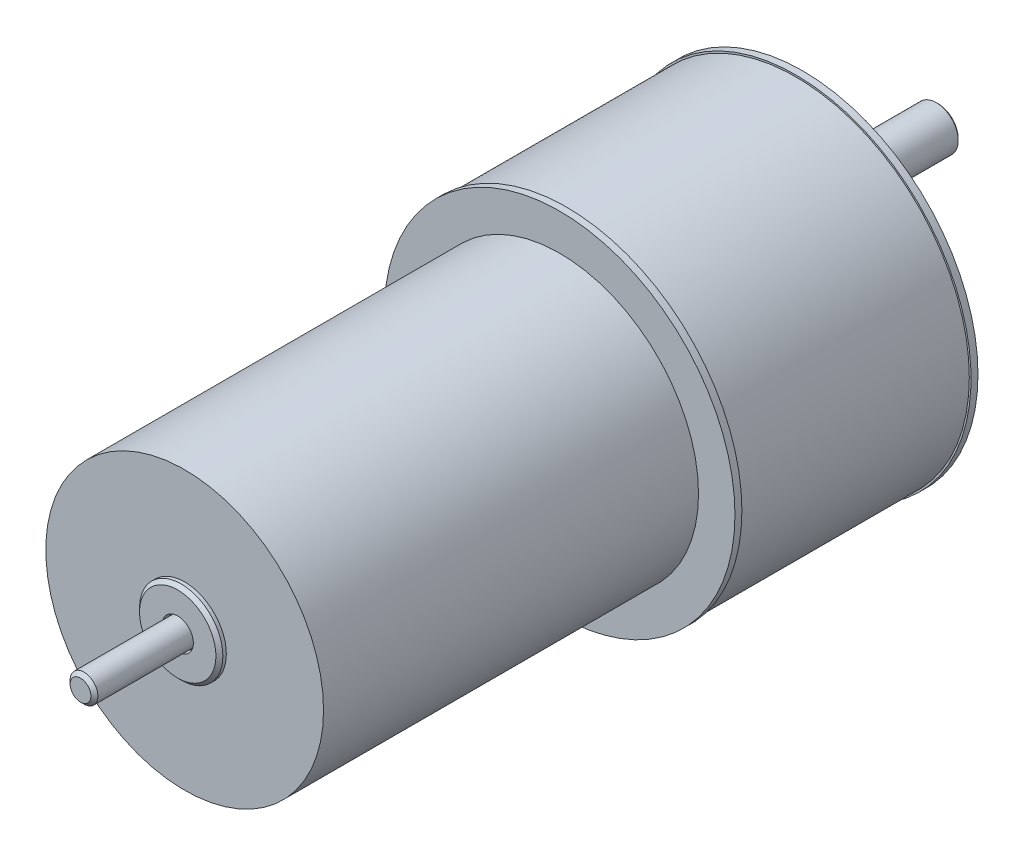
SolidWorks part; units mm, degrees
ref_plane "Plano frontal" through (0, 0, 0) normal (0, 0, 1) x (1, 0, 0)
ref_plane "Plano superior" through (0, 0, 0) normal (0, 1, 0) x (1, 0, 0)
ref_plane "Plano direito" through (0, 0, 0) normal (1, 0, 0) x (0, 0, -1)
sketch "Esboço1" plane through (0, 0, 0) normal (0, 0, 1) x (1, 0, 0)
  circle A0 centre (0, 0) radius 25.25
  dimension "D1" = 50.5
extrude "Ressalto-extrusão1" add sketch "Esboço1" along normal blind 35
sketch "Esboço2" plane through (0, 0, 35) normal (0, 0, 1) x (1, 0, 0)
  circle A0 centre (0, 0) radius 20
  dimension "D1" = 40
extrude "Ressalto-extrusão2" add sketch "Esboço2" along normal blind 54
sketch "Esboço3" plane through (0, 0, 0) normal (0, 0, -1) x (-1, 0, 0)
  circle A0 centre (0, 0) radius 14.25
  dimension "D1" = 28.5
extrude "Ressalto-extrusão3" add sketch "Esboço3" along normal blind 1.5
hole_wizard "Furo roscado de M41" positions "Esboço6" profile "Esboço5" tap size "M4" standard "ISO"
sketch "Esboço6" plane through (0, 0, 0) normal (0, 0, -1) x (-1, 0, 0)
  point P0 (-19, 0)
  point P1 (19, 0)
  dimension "D1" = 38
  dimension "D2" = 19
sketch "Esboço5" plane through (19, 0, 0) normal (1, 0, 0) x (0, 1, 0)
  line L0 (0, 0) -> (0, 12.4914)
  line L1 (0, 12.4914) -> (1.65, 11.5)
  line L2 (1.65, 11.5) -> (1.65, 0)
  line L5 (1.65, 0) -> (0, 0)
  line L10 (0, 12.4914) -> (-1.65, 11.5) construction
  line L11 (0, -6.35) -> (0, 107.95) construction
  dimension "Tap Drill Dia." = 3.3
  dimension "Tap Drill Depth" = 11.5
  dimension "Drill Angle" = 118
cosmetic thread "Rosca de furo1" parameters "D1"=8, "D2"=4
cosmetic thread "Rosca de furo2" parameters "D1"=8, "D2"=4
sketch "Esboço7" plane through (0, 0, -1.5) normal (0, 0, -1) x (-1, 0, 0)
  circle A0 centre (0, 8.5) radius 3.15
  dimension "D1" = 6.3
  dimension "D2" = 8.5
extrude "Ressalto-extrusão4" add sketch "Esboço7" along normal blind 18
chamfer "Chanfro1" distance 0.25 angle 45 1 edges at (-3.15, 8.5, -19.5)
sketch "Esboço8" plane through (0, 0, 89) normal (0, 0, 1) x (1, 0, 0)
  circle A0 centre (0, 0) radius 2
  dimension "D1" = 4
extrude "Ressalto-extrusão5" add sketch "Esboço8" along normal blind 15
chamfer "Chanfro2" distance 0.5 angle 45 1 edges at (2, 0, 104)
sketch "Esboço9" plane through (0, 0, 89) normal (0, 0, 1) x (1, 0, 0)
  circle A0 centre (0, 0) radius 6
  circle A1 centre (0, 0) radius 2.25
  dimension "D1" = 12
  dimension "D2" = 4.5
extrude "Ressalto-extrusão6" add sketch "Esboço9" along normal blind 1
chamfer "Chanfro3" distance 0.5 angle 45 1 edges at (6, 0, 90)
sketch "Esboço10" plane through (0, 0, 0) normal (1, 0, 0) x (0, 0, -1)
  line L0 (0, 0) -> (-89, 0) construction
  line L1 (-1, 40.5404) -> (-34, 40.5404)
  line L2 (-1, 40.5404) -> (-1, 25)
  line L3 (-1, 25) -> (-34, 25)
  line L4 (-34, 40.5404) -> (-34, 25)
  line L5 (-1, 40.5404) -> (-34, 25) construction
  line L6 (-1, 25) -> (-34, 40.5404) construction
  line L7 (-89, 20) -> (-89, -20) construction
  line L8 (0, -25.25) -> (0, 25.25) construction
  point P0 (-17.5, 32.7702)
  dimension "D1" = 25
  dimension "D2" = 17.5
  dimension "D3" = 33
revolve "Corte-Revolução1" cut sketch "Esboço10" angle 360 about L0
